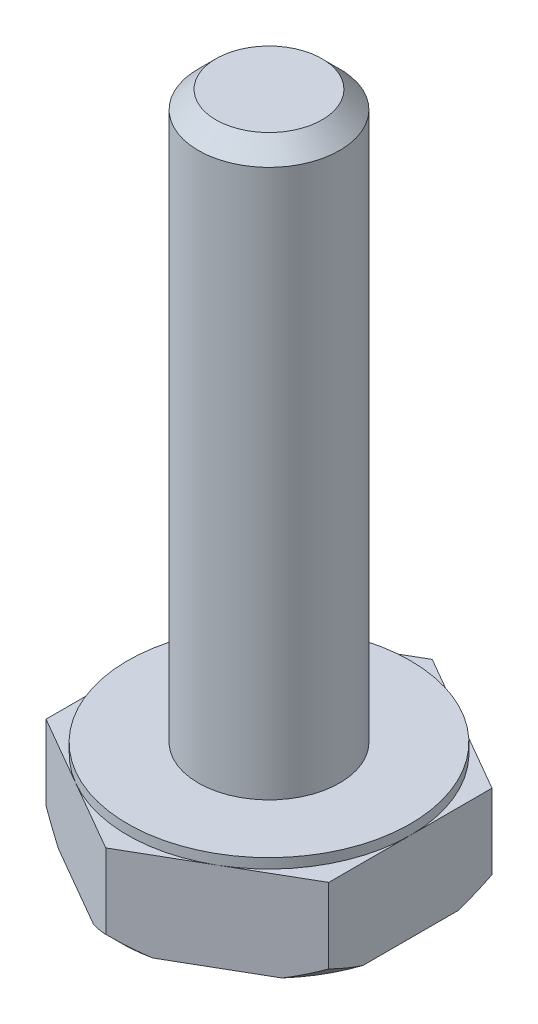
SolidWorks part; units mm, degrees
material "Acier allié"
ref_plane "Plan de face" through (0, 0, 0) normal (0, 0, 1) x (1, 0, 0)
ref_plane "Plan de dessus" through (0, 0, 0) normal (0, 1, 0) x (1, 0, 0)
ref_plane "Plan de droite" through (0, 0, 0) normal (1, 0, 0) x (0, 0, -1)
sketch "Esquisse1" plane through (0, 0, 0) normal (0, 1, 0) x (1, 0, 0)
  circle A0 centre (0, 0) radius 1
  dimension "D_VIS" = 2
extrude "CORPS" add sketch "Esquisse1" along normal blind 8
cosmetic thread "FILETAGE" parameters "LONGUEUR_FILETAGE"=8, "D2"=1.202
sketch "Esquisse2" plane through (0, 0, 0) normal (0, -1, 0) x (-1, 0, 0)
  circle A1 centre (0, 0) radius 2
  dimension "D_APPUI" = 4
extrude "APPUIS" add sketch "Esquisse2" along normal blind 0.14
sketch "Esquisse3" plane through (0, -0.14, 0) normal (0, -1, 0) x (-1, 0, 0)
  line L1 (0, -2.3094) -> (2, -1.1547)
  line L2 (2, -1.1547) -> (2, 1.1547)
  line L3 (2, 1.1547) -> (0, 2.3094)
  line L4 (0, 2.3094) -> (-2, 1.1547)
  line L5 (-2, 1.1547) -> (-2, -1.1547)
  line L6 (-2, -1.1547) -> (0, -2.3094)
  circle A0 centre (0, 0) radius 2 construction
  dimension "L_TETE" = 4
extrude "TETE" add sketch "Esquisse3" along normal blind 1.26
sketch "Esquisse4" plane through (0, 0, 0) normal (1, 0, 0) x (0, 0, -1)
  line L0 (2.3094, -1.2) -> (2.1094, -1.4)
  line L1 (2.3094, -1.4) -> (2.3094, -0.14) construction
  line L2 (2.3094, -1.4) -> (1.1547, -1.4) construction
  line L3 (2.1094, -1.4) -> (2.3094, -1.4)
  line L4 (2.3094, -1.4) -> (2.3094, -1.2)
  line L5 (0, 0) -> (0, -0.4735) construction
  dimension "ANGLE" = 45
  dimension "TAILLE" = 0.2
revolve "CHANFREIN_TETE" cut sketch "Esquisse4" angle 360 about L5
chamfer "CHANFREIN" distance 0.25 angle 45 1 edges at (0, 8, 1)
